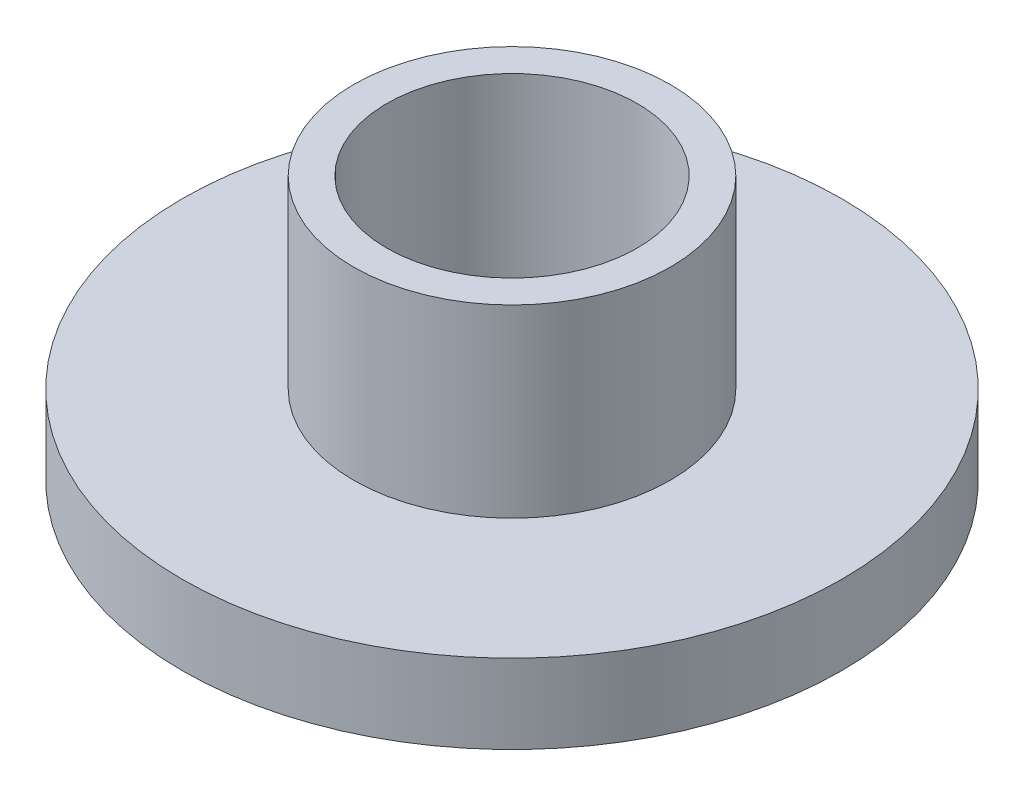
SolidWorks part; units mm, degrees
ref_plane "前视基准面" through (0, 0, 0) normal (0, 0, 1) x (1, 0, 0)
ref_plane "上视基准面" through (0, 0, 0) normal (0, 1, 0) x (1, 0, 0)
ref_plane "右视基准面" through (0, 0, 0) normal (1, 0, 0) x (0, 0, -1)
sketch "草图1" plane through (0, 0, 0) normal (0, 1, 0) x (1, 0, 0)
  line L0 (-14.6896, 0) -> (12.7218, 0) construction
  line L5 (0, 7.9866) -> (0, -8.1972) construction
  circle A0 centre (0, 0) radius 5
  dimension "D1" = 10
extrude "拉伸1" add sketch "草图1" along normal blind 4
sketch "草图2" plane through (0, 4, 0) normal (0, 1, 0) x (-1, 0, 0)
  circle A0 centre (0, 0) radius 1.9
  dimension "D1" = 3.8
extrude "切除-拉伸1" cut sketch "草图2" against normal through all
sketch "草图3" plane through (0, 4, 0) normal (0, 1, 0) x (1, 0, 0)
  circle A0 centre (0, 0) radius 2.4
  circle A2 centre (0, 0) radius 1.9 construction
  dimension "D1" = 0.5
extrude "切除-拉伸2" cut sketch "草图3" against normal offset from surface (2.8 mm away) 1.2 flip side to cut up to face at (0, 0, 1.9)
